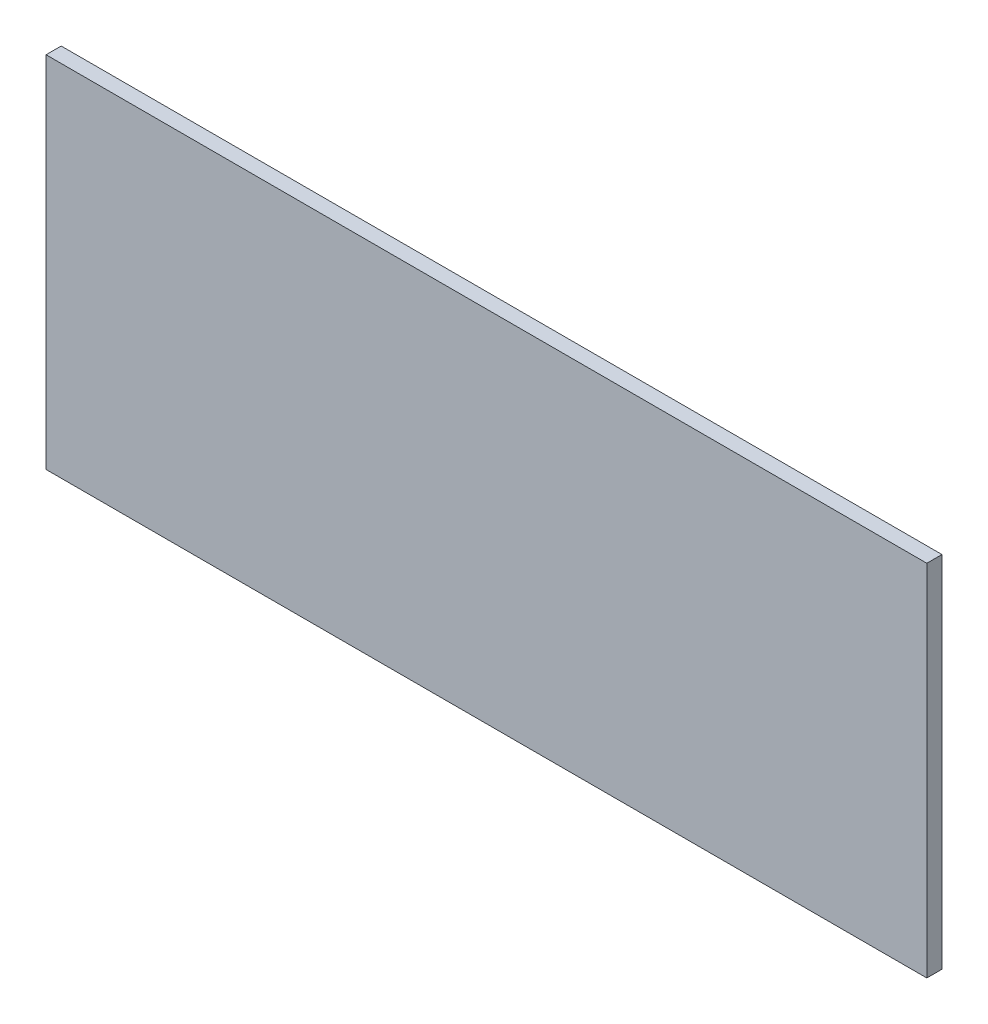
SolidWorks part; units mm, degrees
ref_plane "Alzado" through (0, 0, 0) normal (0, 0, 1) x (1, 0, 0)
ref_plane "Planta" through (0, 0, 0) normal (0, 1, 0) x (1, 0, 0)
ref_plane "Vista lateral" through (0, 0, 0) normal (1, 0, 0) x (0, 0, -1)
sketch "Croquis1" plane through (0, 0, 0) normal (0, 0, 1) x (1, 0, 0)
  line L1 (-81.9114, 39.4593) -> (238.0886, 39.4593)
  line L2 (-81.9114, 39.4593) -> (-81.9114, -91.0407)
  line L3 (-81.9114, -91.0407) -> (238.0886, -91.0407)
  line L4 (238.0886, 39.4593) -> (238.0886, -91.0407)
extrude "Saliente-Extruir1" add sketch "Croquis1" along normal blind 5.5
